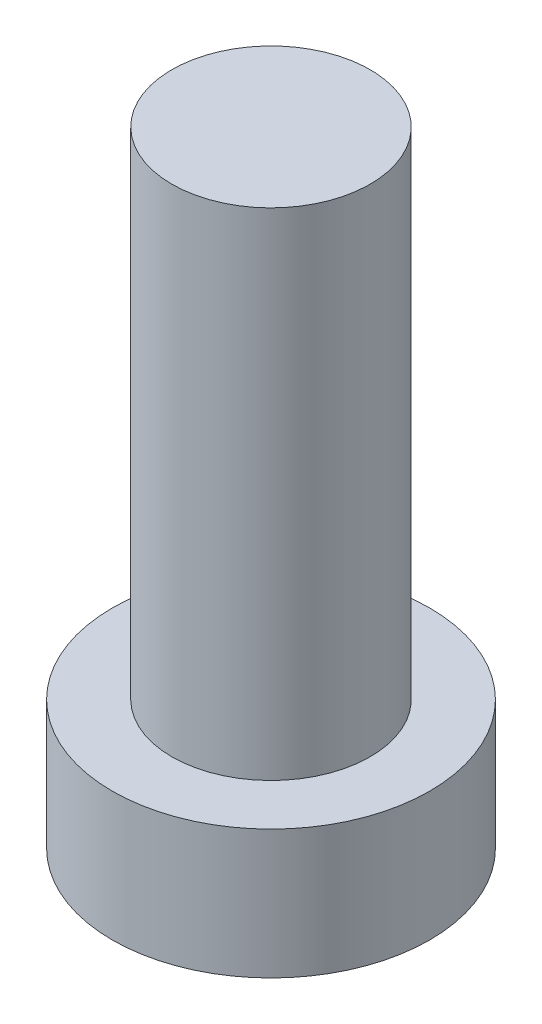
SolidWorks part; units mm, degrees
ref_plane "前视基准面" through (0, 0, 0) normal (0, 0, 1) x (1, 0, 0)
ref_plane "上视基准面" through (0, 0, 0) normal (0, 1, 0) x (1, 0, 0)
ref_plane "右视基准面" through (0, 0, 0) normal (1, 0, 0) x (0, 0, -1)
other "Configuration Table"
sketch "草图1" plane through (0, 0, 0) normal (0, 1, 0) x (1, 0, 0)
  circle A0 centre (0, 0) radius 1.6
  dimension "D1" = 3.2
extrude "凸台-拉伸1" add sketch "草图1" along normal blind 1.3
sketch "草图2" plane through (0, 0, 0) normal (0, 1, 0) x (1, 0, 0)
  circle A0 centre (0, 0) radius 1
extrude "凸台-拉伸2" add sketch "草图2" along normal blind 5 from surface at 1.3 starting at face at (0, 1.3, 1.6)
